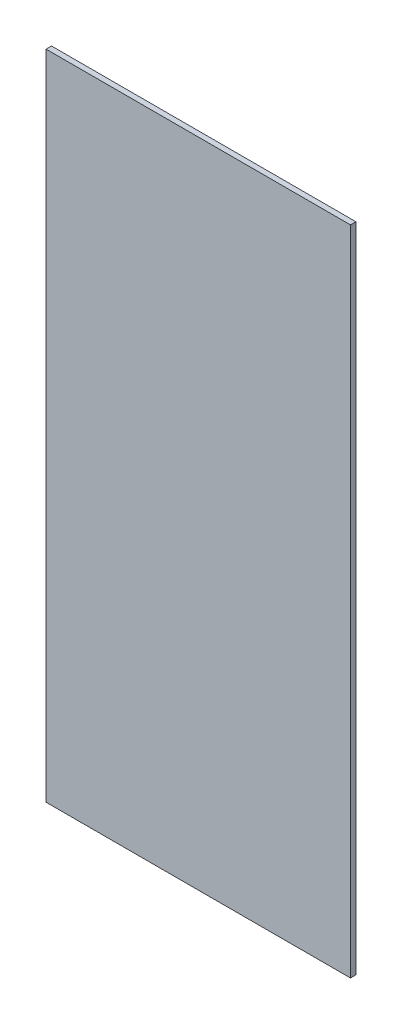
SolidWorks part; units mm, degrees
ref_plane "Front Plane" through (0, 0, 0) normal (0, 0, 1) x (1, 0, 0)
ref_plane "Top Plane" through (0, 0, 0) normal (0, 1, 0) x (1, 0, 0)
ref_plane "Right Plane" through (0, 0, 0) normal (1, 0, 0) x (0, 0, -1)
sketch "Sketch2" plane through (0, 0, 0) normal (0, 0, 1) x (1, 0, 0)
  line L1 (0, 0) -> (177.8, 0)
  line L2 (0, 0) -> (0, 381)
  line L3 (0, 381) -> (177.8, 381)
  line L4 (177.8, 0) -> (177.8, 381)
  dimension "D1" = 177.8
  dimension "D2" = 381
extrude "Boss-Extrude1" add sketch "Sketch2" along normal blind 3.175
